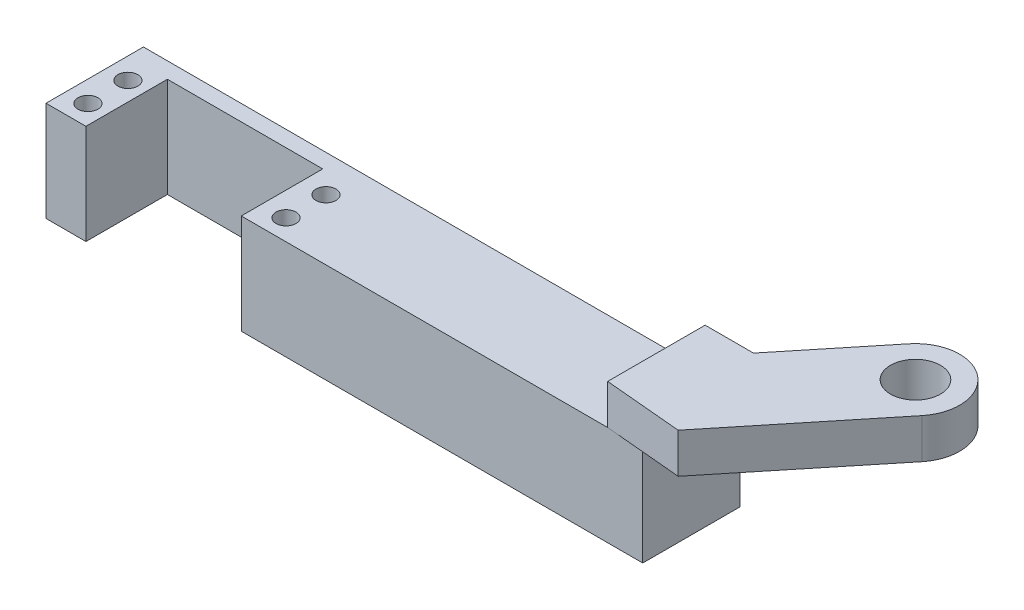
SolidWorks part; units mm, degrees
ref_plane "Front Plane" through (0, 0, 0) normal (0, 0, 1) x (1, 0, 0)
ref_plane "Top Plane" through (0, 0, 0) normal (0, 1, 0) x (1, 0, 0)
ref_plane "Right Plane" through (0, 0, 0) normal (1, 0, 0) x (0, 0, -1)
sketch "Sketch1" plane through (0, 0, 0) normal (0, 1, 0) x (1, 0, 0)
  line L0 (0, 0) -> (-10, 0)
  line L1 (-10, 0) -> (-10, 24.4)
  line L2 (-10, 24.4) -> (139.434, 24.4)
  line L3 (139.434, 24.4) -> (139.434, 0)
  line L4 (139.434, 0) -> (38.8974, 0)
  line L5 (38.8974, 0) -> (38.8974, 20.4)
  line L6 (38.8974, 20.4) -> (0, 20.4)
  line L7 (0, 20.4) -> (0, 0)
  dimension "D1" = 20.4
  dimension "D2" = 10
  dimension "D3" = 4
extrude "Boss-Extrude1" add sketch "Sketch1" along normal blind 25
sketch "Sketch2" plane through (0, 25, 0) normal (0, 1, 0) x (1, 0, 0)
  line L0 (0, 0) -> (0, 20.4) construction
  line L1 (0, 20.4) -> (38.8974, 20.4) construction
  line L2 (20.1, 20.4) -> (20.1, 0) construction
  circle A0 centre (-4.7, 15.2) radius 2.5
  circle A1 centre (-4.7, 5.2) radius 2.5
  circle A2 centre (44.9, 5.2) radius 2.5
  circle A3 centre (44.9, 15.2) radius 2.5
  dimension "D1" = 5
  dimension "D2" = 10
  dimension "D3" = 4.7
  dimension "D4" = 5.2
  dimension "D5" = 24.8
extrude "Cut-Extrude2" cut sketch "Sketch2" against normal blind 10
sketch "Sketch3" plane through (0, 25, 0) normal (0, 1, 0) x (1, 0, 0)
  line L0 (130.6559, 24.4) -> (142.7758, 24.4)
  line L1 (139.434, 24.4) -> (-10, 24.4) construction
  line L2 (142.7758, 24.4) -> (160.2259, 45.8879)
  line L3 (160.2259, 45.8879) -> (177.4162, 31.9279) construction
  line L4 (177.4162, 31.9279) -> (150.0609, -1.757)
  line L5 (150.0609, -1.757) -> (130.6559, 0)
  line L6 (38.8974, 0) -> (139.434, 0) construction
  line L7 (130.6559, 0) -> (130.6559, 24.4)
  arc A0 (177.4162, 31.9279) -> (160.2259, 45.8879) centre (168.821, 38.9079) ccw
  circle A1 centre (168.821, 38.9079) radius 6.2609
  point P6 (168.821, 38.9079)
extrude "Boss-Extrude2" add sketch "Sketch3" along normal blind 10
